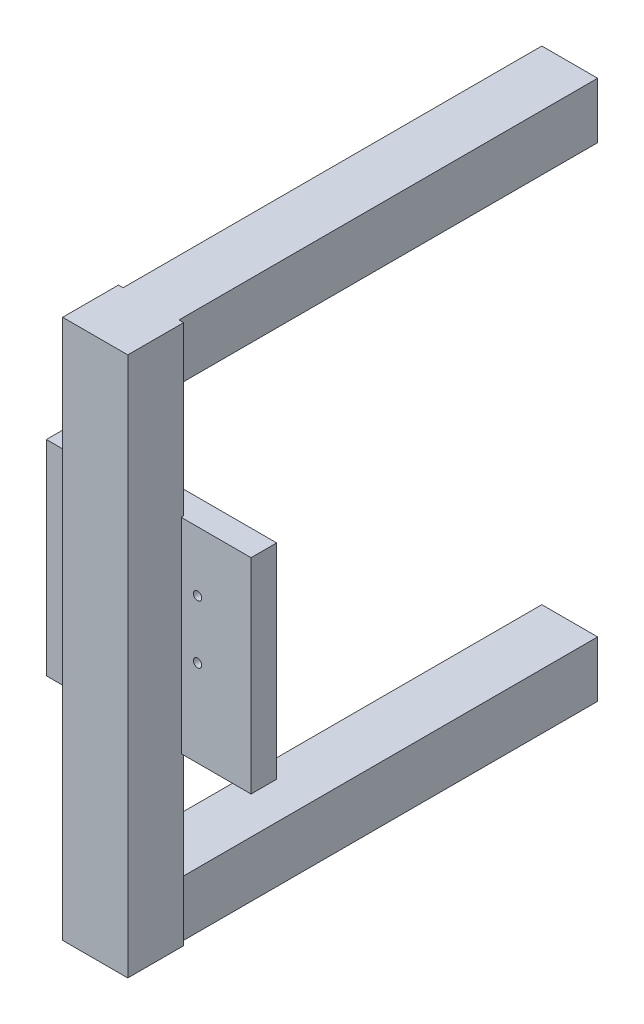
SolidWorks part; units mm, degrees
ref_plane "前视基准面" through (0, 0, 0) normal (0, 0, 1) x (1, 0, 0)
ref_plane "上视基准面" through (0, 0, 0) normal (0, 1, 0) x (1, 0, 0)
ref_plane "右视基准面" through (0, 0, 0) normal (1, 0, 0) x (0, 0, -1)
other "Configuration Table"
sketch "草图1" plane through (0, 0, 0) normal (0, 0, 1) x (1, 0, 0)
  line L1 (13, -58) -> (27, -58)
  line L2 (13, -58) -> (13, 58)
  line L3 (13, 58) -> (27, 58)
  line L4 (27, -58) -> (27, 58)
  dimension "D1" = 14
  dimension "D2" = 116
extrude "Crossbar" add sketch "草图1" along normal blind 12 from offset 133 separate body
sketch "草图2" plane through (0, 0, 0) normal (0, 0, 1) x (1, 0, 0)
  line L1 (14, -58) -> (26, -58)
  line L2 (14, -58) -> (14, -46)
  line L3 (14, -46) -> (26, -46)
  line L4 (26, -58) -> (26, -46)
  dimension "D1" = 12
  dimension "D2" = 12
extrude "Post" add sketch "草图2" along normal blind 102 from offset 43
sketch "草图3" plane through (0, 0, 0) normal (0, 0, 1) x (1, 0, 0)
  line L1 (14, 46) -> (26, 46)
  line L2 (14, 46) -> (14, 58)
  line L3 (14, 58) -> (26, 58)
  line L4 (26, 46) -> (26, 58)
  dimension "D1" = 12
  dimension "D2" = 12
extrude "凸台-拉伸3" add sketch "草图3" along normal blind 102 from offset 43
sketch "草图4" plane through (0, 0, 0) normal (0, 0, 1) x (1, 0, 0)
  line L1 (-2, -22) -> (42, -22)
  line L2 (-2, -22) -> (-2, 22)
  line L3 (-2, 22) -> (42, 22)
  line L4 (42, -22) -> (42, 22)
  dimension "D1" = 44
  dimension "D2" = 44
extrude "CameraPlate" add sketch "草图4" along normal blind 5.5 from offset 128
sketch "草图5" plane through (0, 0, 0) normal (0, 0, 1) x (1, 0, 0)
  line L1 (7.2, -9.25) -> (32.8, -9.25)
  line L2 (7.2, -9.25) -> (7.2, 15.05)
  line L3 (7.2, 15.05) -> (32.8, 15.05)
  line L4 (32.8, -9.25) -> (32.8, 15.05)
  dimension "D1" = 25.6
  dimension "D2" = 24.3
extrude "CameraRecess" cut sketch "草图5" along normal blind 1.6 from offset 128
sketch "草图6" plane through (0, 0, 0) normal (0, 0, 1) x (1, 0, 0)
  circle A0 centre (20, 0) radius 5
  dimension "D1" = 10
extrude "LensWindow" cut sketch "草图6" along normal blind 7 from offset 127
sketch "草图7" plane through (0, 0, 0) normal (0, 0, 1) x (1, 0, 0)
  circle A0 centre (9.5, -3.35) radius 0.9
  dimension "D1" = 1.8
extrude "CamScrew" cut sketch "草图7" along normal blind 7 from offset 127
sketch "草图8" plane through (0, 0, 0) normal (0, 0, 1) x (1, 0, 0)
  circle A0 centre (9.5, 9.15) radius 0.9
  dimension "D1" = 1.8
extrude "切除-拉伸4" cut sketch "草图8" along normal blind 7 from offset 127
sketch "草图9" plane through (0, 0, 0) normal (0, 0, 1) x (1, 0, 0)
  circle A0 centre (30.5, -3.35) radius 0.9
  dimension "D1" = 1.8
extrude "切除-拉伸5" cut sketch "草图9" along normal blind 7 from offset 127
sketch "草图10" plane through (0, 0, 0) normal (0, 0, 1) x (1, 0, 0)
  circle A0 centre (30.5, 9.15) radius 0.9
  dimension "D1" = 1.8
extrude "切除-拉伸6" cut sketch "草图10" along normal blind 7 from offset 127
